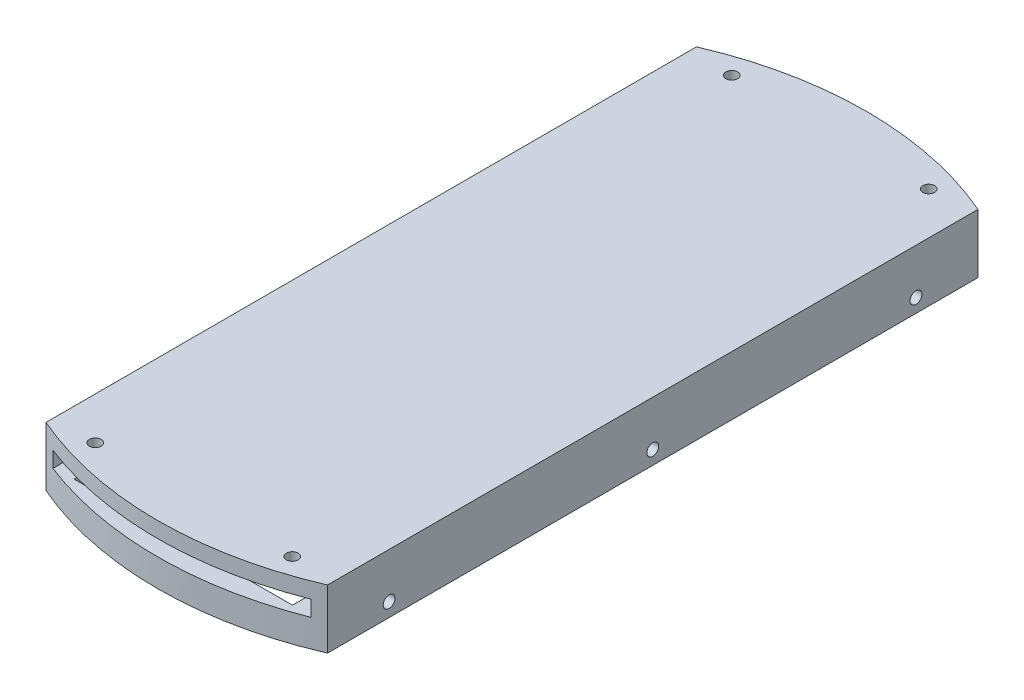
SolidWorks part; units mm, degrees
ref_plane "Plano frontal" through (0, 0, 0) normal (0, 0, 1) x (1, 0, 0)
ref_plane "Plano superior" through (0, 0, 0) normal (0, 1, 0) x (1, 0, 0)
ref_plane "Plano direito" through (0, 0, 0) normal (1, 0, 0) x (0, 0, -1)
sketch "Esboço2" plane through (0, 0, 0) normal (0, 1, 0) x (1, 0, 0)
  line L2 (-35.75, -82.595) -> (-35.75, 82.595)
  line L3 (35.75, -82.595) -> (35.75, 82.595)
  arc A0 (-35.75, -82.595) -> (35.75, -82.595) centre (0, 0) ccw
  arc A1 (35.75, 82.595) -> (-35.75, 82.595) centre (0, 0) ccw
extrude "Ressalto-extrusão1" add sketch "Esboço2" along normal blind 15
sketch "Esboço3" plane through (0, 0, 0) normal (0, -1, 0) x (-1, 0, 0)
  line L9 (27.75, 69.5) -> (27.75, 83.5)
  line L13 (28.75, -69.5) -> (27.75, -69.5)
  line L14 (28.75, -64.4) -> (27.75, -64.4)
  line L15 (28.75, -2.55) -> (27.75, -2.55)
  line L16 (28.75, 2.55) -> (27.75, 2.55)
  line L17 (28.75, 64.4) -> (27.75, 64.4)
  line L18 (28.75, 69.5) -> (27.75, 69.5)
  line L21 (-27.75, -83.5) -> (-27.75, 83.5)
  line L28 (27.75, -83.5) -> (27.75, -69.5)
  line L29 (28.75, -69.5) -> (28.75, -64.4)
  line L30 (28.75, -2.55) -> (28.75, 2.55)
  line L31 (27.75, -64.4) -> (27.75, -2.55)
  line L32 (28.75, 64.4) -> (28.75, 69.5)
  line L35 (27.75, 83.5) -> (-27.75, 83.5)
  line L36 (27.75, 2.55) -> (27.75, 64.4)
  line L37 (27.75, -83.5) -> (-27.75, -83.5)
extrude "Corte-extrusão1" cut sketch "Esboço3" against normal blind 7 contours L14 L31 L15 L30 L16 L36 L17 L32 L18 L9 L35 L21 L37 L28 L13 L29
ref_plane "Plano1" through (0, 0, 90) normal (0, 0, 1) x (1, 0, 0)
ref_plane "Plano2" through (0, 0, -90) normal (0, 0, -1) x (-1, 0, 0)
sketch "Esboço4" plane through (0, 0, -90) normal (0, 0, -1) x (-1, 0, 0)
  line L0 (0, 15) -> (-32.75, 15)
  line L1 (35.75, 15) -> (-35.75, 15) construction
  line L5 (-32.75, 11) -> (32.75, 11)
  line L8 (32.75, 7) -> (-32.75, 7)
  line L9 (32.75, 7) -> (32.75, 11)
  line L11 (-32.75, 7) -> (-32.75, 11)
extrude "Corte-extrusão3" cut sketch "Esboço4" against normal blind 14.5 contours L11 L8 L9 L5
sketch "Esboço5" plane through (0, 0, 90) normal (0, 0, 1) x (1, 0, 0)
  line L3 (32.75, 11) -> (-32.75, 11)
  line L5 (-32.75, 7) -> (32.75, 7)
  line L8 (32.75, 7) -> (32.75, 11)
  line L11 (-32.75, 7) -> (-32.75, 11)
extrude "Corte-extrusão4" cut sketch "Esboço5" against normal blind 14.5 contours L5 L8 L3 L11
sketch "Esboço6" plane through (0, 15, 0) normal (0, 1, 0) x (1, 0, 0)
  circle A1 centre (-25.01, 80.825) radius 1.5
  circle A2 centre (25.01, 80.825) radius 1.5
  circle A3 centre (-25.01, -80.825) radius 1.5
  circle A4 centre (25.01, -80.825) radius 1.5
extrude "Corte-extrusão5" cut sketch "Esboço6" against normal through all
sketch "Esboço7" plane through (35.75, 0, 0) normal (1, 0, 0) x (0, 0, -1)
  circle A0 centre (-66.955, 3.5) radius 1.5
  circle A1 centre (-0.005, 3.5) radius 1.5
  circle A2 centre (66.845, 3.5) radius 1.5
extrude "Corte-extrusão6" cut sketch "Esboço7" against normal blind 14.5
